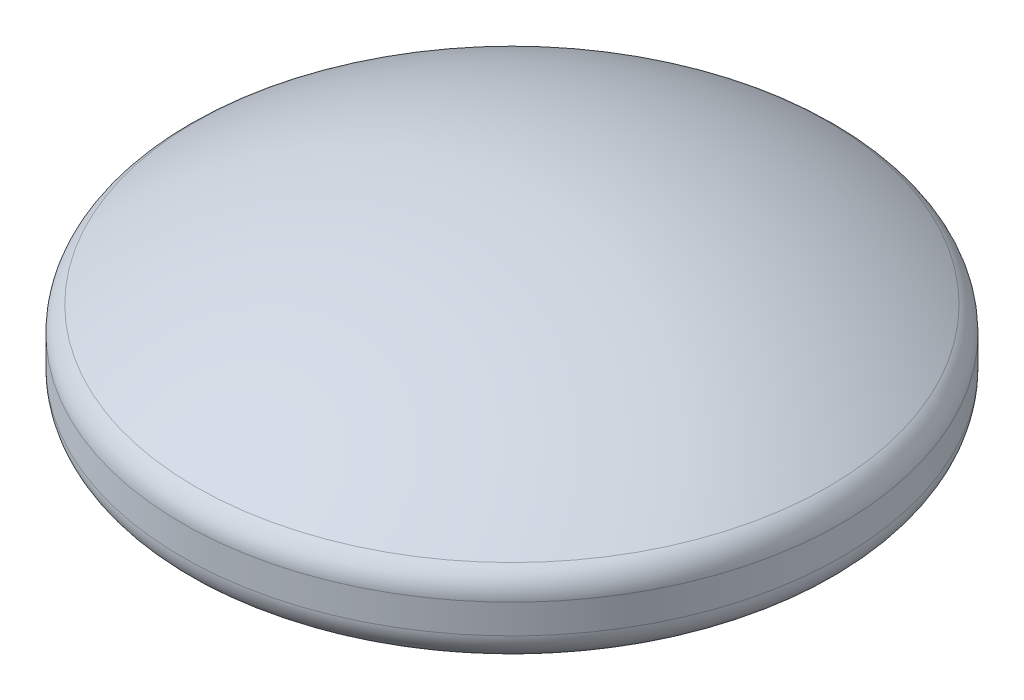
SolidWorks part; units mm, degrees
ref_plane "Front Plane" through (0, 0, 0) normal (0, 0, 1) x (1, 0, 0)
ref_plane "Top Plane" through (0, 0, 0) normal (0, 1, 0) x (1, 0, 0)
ref_plane "Right Plane" through (0, 0, 0) normal (1, 0, 0) x (0, 0, -1)
sketch "Sketch1" plane through (0, 0, 0) normal (1, 0, 0) x (0, 0, -1)
  line L0 (0, 3.81) -> (0, 16.764)
  line L1 (9.906, 0) -> (20.32, 0)
  line L2 (20.32, 0) -> (20.32, 1.524)
  line L3 (20.32, 1.524) -> (27.94, 1.524)
  line L4 (27.94, 1.524) -> (27.94, 7.874)
  line L5 (0, 3.81) -> (9.906, 3.81)
  line L6 (9.906, 3.81) -> (9.906, 0)
  arc A0 (27.94, 7.874) -> (0, 16.764) centre (0, -31.5867) ccw
  dimension "D1" = 3.81
  dimension "D2" = 27.94
  dimension "D3" = 1.524
  dimension "D4" = 9.906
  dimension "D5" = 20.32
  dimension "D6" = 16.764
  dimension "D7" = 6.35
revolve "Revolve1" add sketch "Sketch1" angle 360 about L0
fillet "Fillet1" radius 2.54 2 edges at (0, 1.524, -27.94) (0, 7.874, -27.94)
